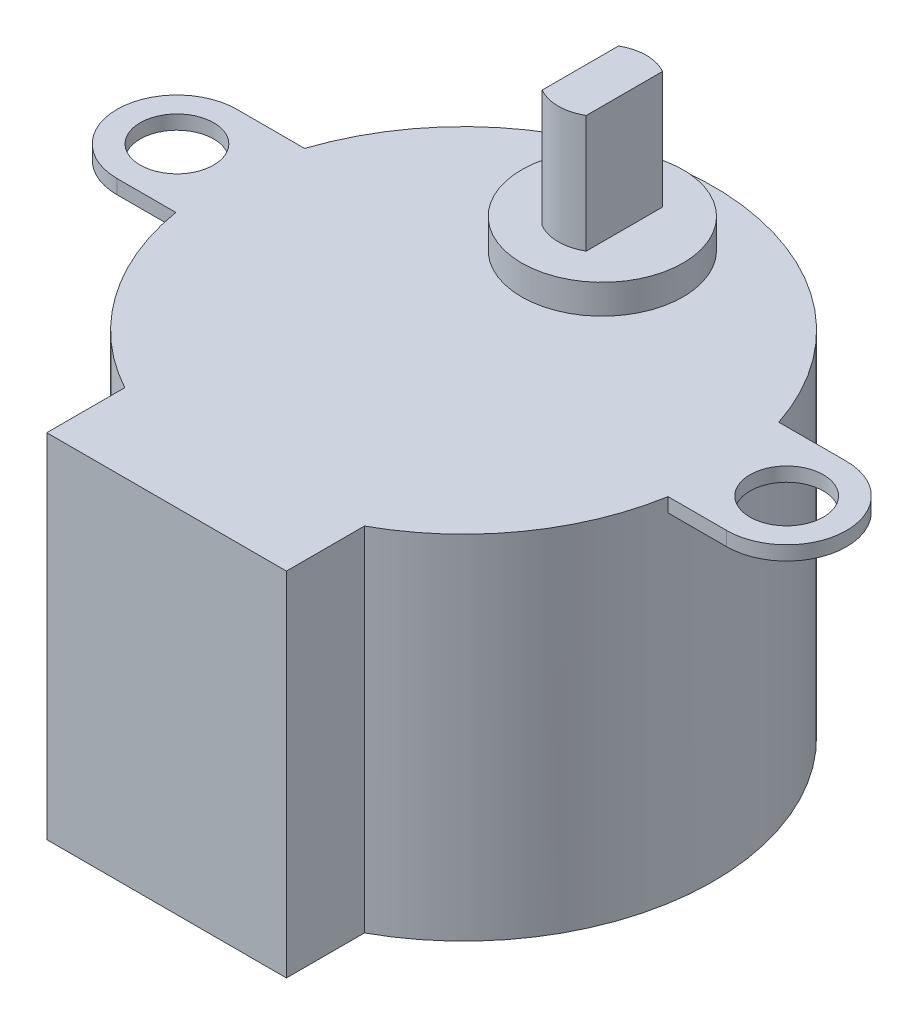
SolidWorks part; units mm, degrees
ref_plane "Front" through (0, 0, 0) normal (0, 0, 1) x (1, 0, 0)
ref_plane "Top" through (0, 0, 0) normal (0, 1, 0) x (1, 0, 0)
ref_plane "Right" through (0, 0, 0) normal (1, 0, 0) x (0, 0, -1)
sketch "Sketch2" plane through (0, 0, 0) normal (0, 1, 0) x (1, 0, 0)
  line L0 (-6.477, -11.8376) -> (-6.477, -16.0535)
  line L1 (-6.477, -16.0535) -> (6.477, -16.0535)
  line L2 (0, -31.0683) -> (0, 31.0683) construction
  line L3 (6.477, -11.8376) -> (6.477, -16.0535)
  circle A0 centre (0, 0) radius 13.4937
  point P9 (0, -16.0535)
  dimension "D1" = 26.9875
  dimension "D2" = 6.477
extrude "Boss-Extrude1" add sketch "Sketch2" along normal blind 19.05 contours A0 L0 L1 L3
sketch "Sketch3" plane through (0, 19.05, 0) normal (0, 1, 0) x (1, 0, 0)
  line L0 (-16.4791, -2.2543) -> (-13.3041, -2.2543)
  line L1 (0, 13.4937) -> (-20.6176, 13.4937) construction
  line L2 (-12.816, 4.2227) -> (-16.4791, 4.2227)
  line L3 (0, -10.4775) -> (0, 10.4775) construction
  line L4 (6.477, -16.0535) -> (6.477, -11.8376)
  line L5 (-6.477, -11.8376) -> (-6.477, -16.0535)
  line L6 (-6.477, -16.0535) -> (6.477, -16.0535)
  line L7 (6.477, -16.0535) -> (6.477, -11.8376)
  line L8 (-6.477, -11.8376) -> (-6.477, -16.0535)
  line L9 (-6.477, -16.0535) -> (6.477, -16.0535)
  line L10 (12.816, 4.2227) -> (16.4791, 4.2227)
  line L11 (16.4791, -2.2543) -> (13.3041, -2.2543)
  arc A0 (6.477, -11.8376) -> (-6.477, -11.8376) centre (0, 0) ccw construction
  arc A1 (-16.4791, -2.2543) -> (-16.4791, 4.2227) centre (-16.4791, 0.9842) cw
  arc A2 (6.477, -11.8376) -> (-6.477, -11.8376) centre (0, 0) ccw
  arc A3 (6.477, -11.8376) -> (-6.477, -11.8376) centre (0, 0) ccw
  circle A4 centre (-16.4791, 0.9842) radius 1.9844
  circle A5 centre (16.4791, 0.9842) radius 1.9844
  arc A6 (16.4791, -2.2543) -> (16.4791, 4.2227) centre (16.4791, 0.9842) ccw
  arc M9 (6.477, -11.8376) -> (-6.477, -11.8376) centre (0, 0) ccw
  dimension "D5" = 3.9688
  dimension "D2" = 15.748
  dimension "D3" = 6.477
  dimension "D4" = 3.175
  dimension "D1" = 0
extrude "Boss-Extrude2" add sketch "Sketch3" against normal blind 0.762 contours A1 L0 L2 A4 M9 | L11 A6 L10 A5 M9
sketch "Sketch5" plane through (0, 19.05, 0) normal (0, 1, 0) x (1, 0, 0)
  line L0 (0, -10.4775) -> (0, 10.4775) construction
  circle A0 centre (0, 7.5011) radius 4.3656
  point P4 (0, 7.9764)
  point P8 (0, 7.5011)
  dimension "D1" = 8.7312
extrude "Boss-Extrude3" add sketch "Sketch5" along normal blind 1.5875
sketch "Sketch6" plane through (0, 20.6375, 0) normal (0, 1, 0) x (1, 0, 0)
  line L0 (-1.1906, 9.5634) -> (-1.1906, 5.4389)
  line L1 (0, -11.3506) -> (0, 11.3506) construction
  line L2 (1.1906, 9.5634) -> (1.1906, 5.4389)
  circle A0 centre (0, 7.5011) radius 2.3813
  dimension "D1" = 4.7625
  dimension "D2" = 2.3813
extrude "Boss-Extrude4" add sketch "Sketch6" along normal blind 6.35 contours L2 A0 L0
